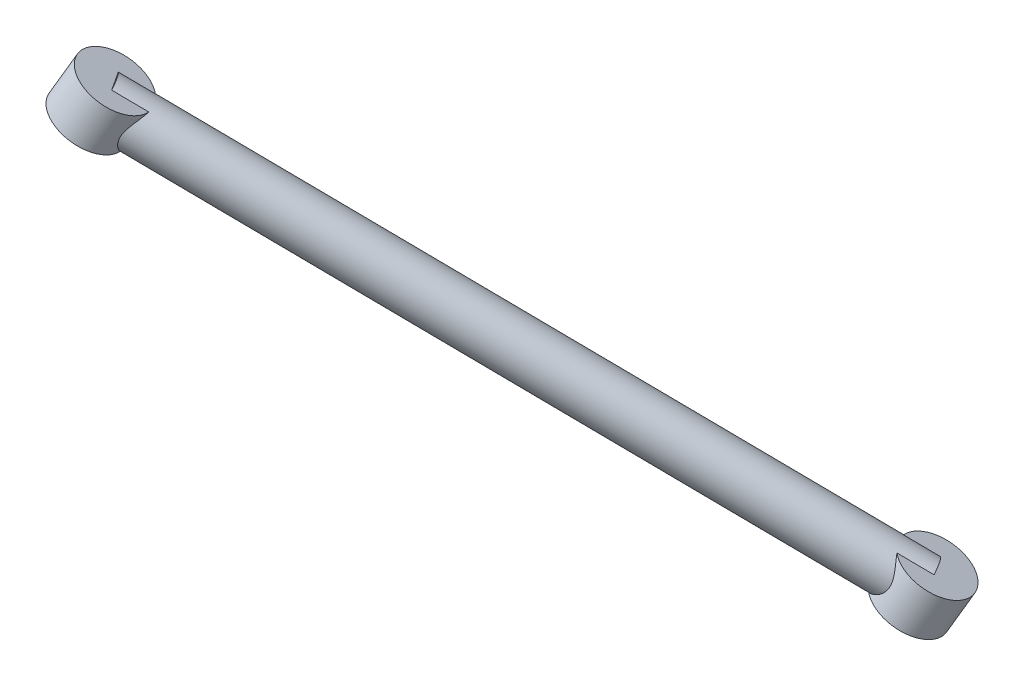
SolidWorks part; units mm, degrees
ref_plane "Plano frontal" through (0, 0, 0) normal (0, 0, 1) x (1, 0, 0)
ref_plane "Plano superior" through (0, 0, 0) normal (0, 1, 0) x (1, 0, 0)
ref_plane "Plano direito" through (0, 0, 0) normal (1, 0, 0) x (0, 0, -1)
sketch3d "SUSP_FR_pullrod_eixo"
  line L0 (510.46, -91.34, -282.35) -> (343.0563, 19.7951, -174.0819)
sweep "SUSP_FR_pullrod" add path "SUSP_FR_pullrod_eixo" circular profile diameter 16 parameters "D3"=16
sketch3d "SUSP_FR_pullrod_rod_end_mount_eixo"
  line L0 (507.6592, -97.4534, -280.4053) -> (513.2608, -85.2266, -284.2947)
sweep "SUSP_FR_pullrod_rod_end_mount" add path "SUSP_FR_pullrod_rod_end_mount_eixo" circular profile diameter 22 parameters "D3"=22
sketch3d "SUSP_FR_pullrod_rod_end_rocker_eixo"
  line L0 (340.2555, 13.6817, -172.1372) -> (345.8571, 25.9085, -176.0266)
sweep "SUSP_FR_pullrod_rod_end_rocker" add path "SUSP_FR_pullrod_rod_end_rocker_eixo" circular profile diameter 22 parameters "D3"=22
sketch3d "REF_SKETCH"
  line L0 (506.46, -93.74, -284.15) -> (514.46, -88.94, -280.55)
  line L1 (512.86, -94.34, -285.55) -> (508.06, -88.34, -279.15)
  line L2 (339.0563, 17.3951, -175.8819) -> (347.0563, 22.1951, -172.2819)
  line L3 (345.4563, 16.7951, -177.2819) -> (340.6563, 22.7951, -170.8819)
ref_point "P_MOUNT"
ref_point "P_ROCKER"
